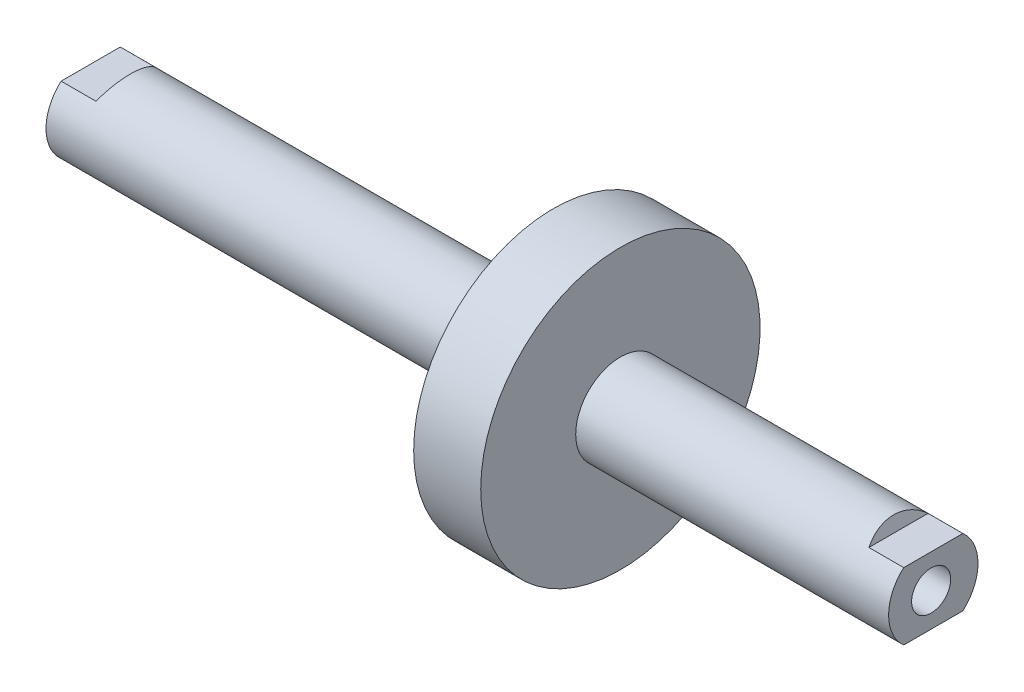
SolidWorks part; units mm, degrees
ref_plane "前视基准面" through (0, 0, 0) normal (0, 0, 1) x (1, 0, 0)
ref_plane "上视基准面" through (0, 0, 0) normal (0, 1, 0) x (1, 0, 0)
ref_plane "右视基准面" through (0, 0, 0) normal (1, 0, 0) x (0, 0, -1)
sketch "草图1" plane through (0, 0, 0) normal (0, 1, 0) x (1, 0, 0)
  line L0 (-41.4, 0.193) -> (-41.4, 4.193)
  line L1 (-41.4, 0.193) -> (34, 0.193) construction
  line L2 (-41.4, 4.193) -> (0, 4.193)
  line L3 (0, 4.193) -> (0, 12.693)
  line L4 (0, 12.693) -> (6, 12.693)
  line L5 (6, 12.693) -> (6, 4.193)
  line L6 (6, 4.193) -> (34, 4.193)
  line L7 (34, 4.193) -> (34, 0.193)
  line L8 (-41.4, 0.193) -> (34, 0.193)
  dimension "D1" = 4
  dimension "D2" = 12.5
  dimension "D3" = 4
  dimension "D4" = 28
  dimension "D5" = 75.4
  dimension "D6" = 6
revolve "旋转1" add sketch "草图1" angle 360 about L1
sketch "草图2" plane through (34, 0, 0) normal (1, 0, 0) x (0, 0, -1)
  circle A0 centre (0, 0) radius 1.75
  dimension "D1" = 3.5
extrude "拉伸1" cut sketch "草图2" against normal blind 12
sketch "草图3" plane through (-41.4, 0, 0) normal (-1, 0, 0) x (0, 0, 1)
  circle A0 centre (-0.193, 0) radius 1.75
  dimension "D1" = 3.5
extrude "拉伸2" cut sketch "草图3" against normal blind 12
sketch "草图4" plane through (0, 0, 0) normal (0, 0, 1) x (1, 0, 0)
  line L0 (-41.4, 4) -> (-41.4, 3)
  line L1 (-41.4, 4) -> (-41.4, -4) construction
  line L2 (-41.4, 3) -> (-38.2827, 3)
  line L3 (-38.2827, 3) -> (-37.8558, 4)
  line L4 (0, 4) -> (-41.4, 4) construction
  line L5 (34, 4) -> (30.4558, 4)
  line L6 (-41.4, 0) -> (-27.2761, 0) construction
  line L7 (-41.4, -4) -> (-41.4, -3)
  line L8 (-41.4, -4) -> (-37.8558, -4)
  line L9 (-38.2827, -3) -> (-37.8558, -4)
  line L10 (-41.4, -3) -> (-38.2827, -3)
  line L11 (30.8827, -3) -> (34, -3)
  line L12 (-3.7, 4) -> (-3.7, -8.0335) construction
  line L13 (34, -4) -> (34, -3)
  line L14 (34, -4) -> (30.4558, -4)
  line L15 (30.8827, -3) -> (30.4558, -4)
  line L16 (34, 4) -> (34, 3)
  line L17 (-41.4, 4) -> (-37.8558, 4)
  line L18 (30.8827, 3) -> (30.4558, 4)
  line L19 (34, 3) -> (30.8827, 3)
  dimension "D1" = 1
extrude "拉伸5" cut sketch "草图4" against normal mid plane 12
